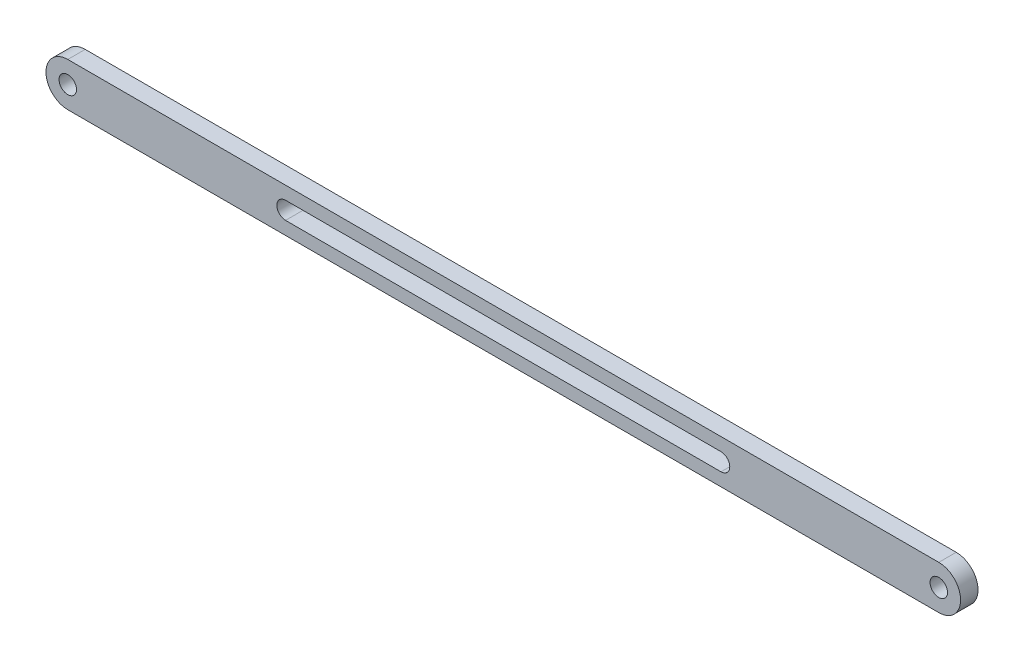
SolidWorks part; units mm, degrees
material "1060 Alloy"
ref_plane "Front Plane" through (0, 0, 0) normal (0, 0, 1) x (1, 0, 0)
ref_plane "Top Plane" through (0, 0, 0) normal (0, 1, 0) x (1, 0, 0)
ref_plane "Right Plane" through (0, 0, 0) normal (1, 0, 0) x (0, 0, -1)
sketch "Sketch1" plane through (0, 0, 0) normal (0, 0, 1) x (1, 0, 0)
  line L0 (0, 0) -> (200, 0) construction
  line L1 (0, 5) -> (200, 5)
  line L2 (0, -5) -> (200, -5)
  line L3 (50, 0) -> (150, 0) construction
  line L4 (50, 2) -> (150, 2)
  line L5 (50, -2) -> (150, -2)
  arc A0 (0, 5) -> (0, -5) centre (0, 0) ccw
  arc A1 (200, -5) -> (200, 5) centre (200, 0) ccw
  circle A2 centre (0, 0) radius 2
  arc A3 (50, 2) -> (50, -2) centre (50, 0) ccw
  circle A4 centre (200, 0) radius 2
  arc A5 (150, -2) -> (150, 2) centre (150, 0) ccw
  point P3 (100, 0)
  point P14 (100, 0)
  dimension "D1" = 5
  dimension "D3" = 4
  dimension "D4" = 100
  dimension "D5" = 2
  dimension "D2" = 200
extrude "Boss-Extrude1" add sketch "Sketch1" along normal blind 4
ref_plane "Plane1" through (0, 0, 0) normal (0, -1, 0) x (-1, 0, 0)
